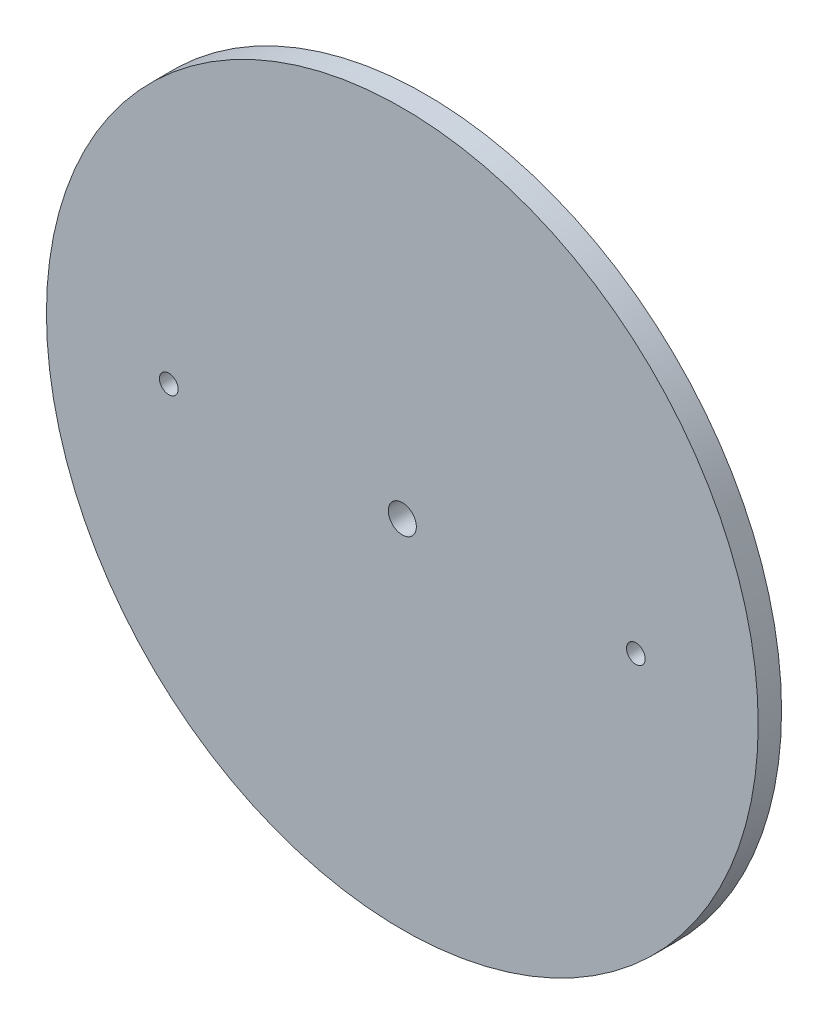
SolidWorks part; units mm, degrees
material "1060 Alloy"
ref_plane "Front Plane" through (0, 0, 0) normal (0, 0, 1) x (1, 0, 0)
ref_plane "Top Plane" through (0, 0, 0) normal (0, 1, 0) x (1, 0, 0)
ref_plane "Right Plane" through (0, 0, 0) normal (1, 0, 0) x (0, 0, -1)
ref_plane "Plane1" through (0, 0, -5) normal (0, 0, -1) x (-1, 0, 0)
sketch "Sketch1" plane through (0, 0, -5) normal (0, 0, -1) x (-1, 0, 0)
  circle A0 centre (50, 0) radius 2
  circle A1 centre (-50, 0) radius 2
  circle A2 centre (0, 0) radius 3
  circle A3 centre (0, 0) radius 76.2
extrude "Boss-Extrude1" add sketch "Sketch1" against normal blind 5
